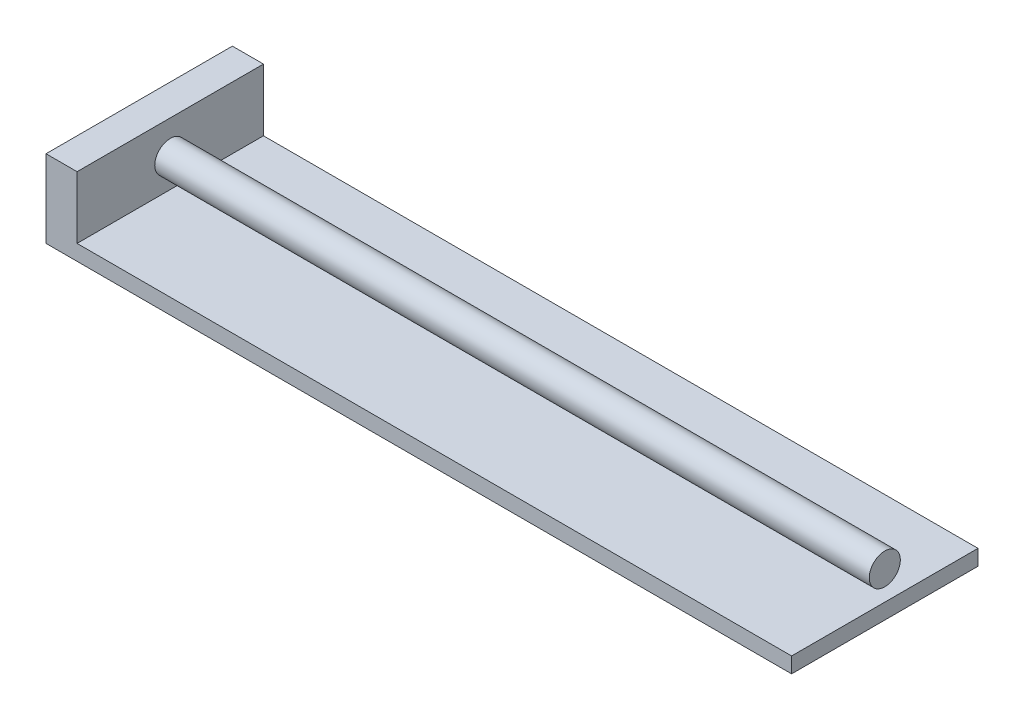
SolidWorks part; units mm, degrees
ref_plane "Front Plane" through (0, 0, 0) normal (0, 0, 1) x (1, 0, 0)
ref_plane "Top Plane" through (0, 0, 0) normal (0, 1, 0) x (1, 0, 0)
ref_plane "Right Plane" through (0, 0, 0) normal (1, 0, 0) x (0, 0, -1)
sketch "Sketch1" plane through (0, 0, 0) normal (0, 1, 0) x (1, 0, 0)
  line L1 (-120, -30) -> (120, -30)
  line L2 (-120, -30) -> (-120, 30)
  line L3 (-120, 30) -> (120, 30)
  line L4 (120, -30) -> (120, 30)
  line L5 (-120, -30) -> (120, 30) construction
  line L6 (-120, 30) -> (120, -30) construction
  point P0 (0, 0)
  dimension "D1" = 60
  dimension "D2" = 240
extrude "Boss-Extrude1" add sketch "Sketch1" along normal blind 5
sketch "Sketch2" plane through (0, 5, 0) normal (0, 1, 0) x (1, 0, 0)
  line L0 (-120, -30) -> (120, -30) construction
  line L1 (-120, 30) -> (-110, 30)
  line L2 (-120, 30) -> (-120, -30)
  line L3 (-120, -30) -> (-110, -30)
  line L4 (-110, 30) -> (-110, -30)
  dimension "D1" = 10
extrude "Boss-Extrude2" add sketch "Sketch2" along normal blind 20
sketch "Sketch3" plane through (-110, 0, 0) normal (1, 0, 0) x (0, 0, -1)
  line L0 (0, 5) -> (0, 14.27) construction
  line L1 (-30, 5) -> (30, 5) construction
  circle A0 centre (0, 14.27) radius 5
  dimension "D2" = 10
  dimension "D1" = 9.27
extrude "Boss-Extrude3" add sketch "Sketch3" along normal through all
